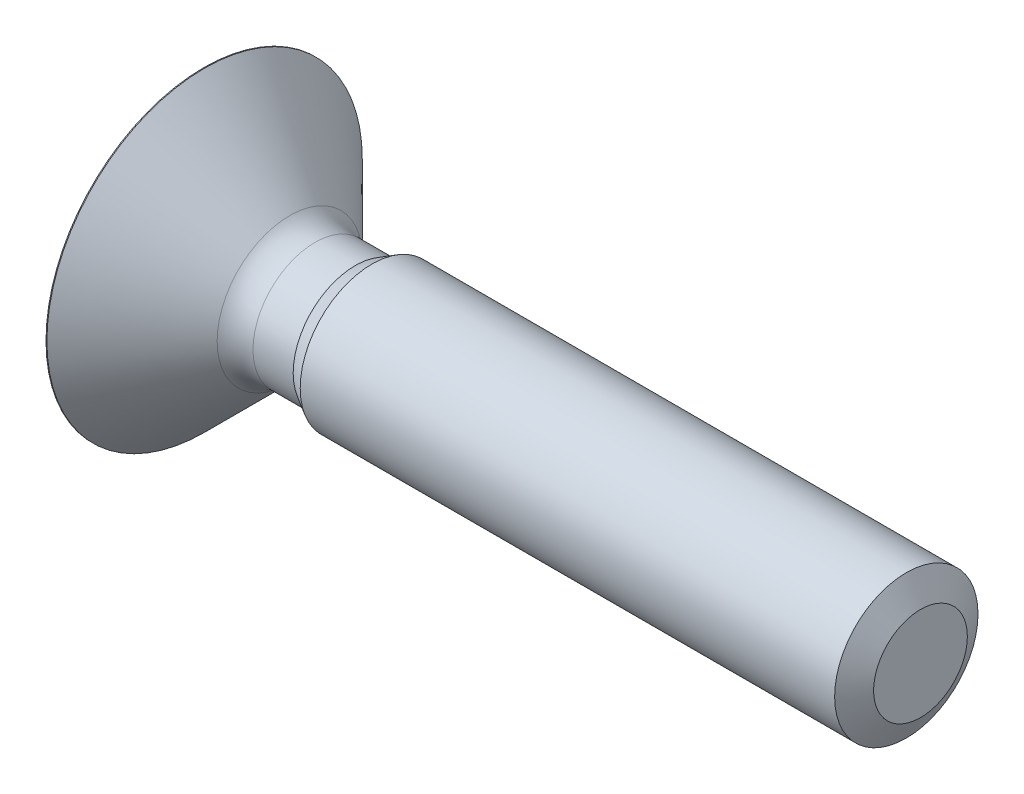
SolidWorks part; units mm, degrees
revolve "基体-旋转" add sketch "草图1" angle 360 about L0
sketch "草图1" plane through (0, 0, 0) normal (0, 0, 1) x (1, 0, 0)
  line L0 (0, 0) -> (4.4175, 0) construction
  line L1 (0, 0) -> (0, 2.2)
  line L2 (0, 2.2) -> (0.0124, 2.2)
  line L3 (0.0124, 2.2) -> (1.2, 1.0124)
  line L4 (1.5536, 0.866) -> (2.1144, 0.866)
  line L5 (2.1144, 0.866) -> (2.3464, 1)
  line L6 (2.3464, 1) -> (10, 1)
  line L7 (10, 1) -> (10, 0)
  line L8 (0, 0) -> (10, 0)
  arc A0 (1.5536, 0.866) -> (1.2, 1.0124) centre (1.5536, 1.366) cw
  point P12 (1.3464, 0.866)
  dimension "D2" = 0.5
  dimension "D1" = 1.732
  dimension "d" = 2
  dimension "dk" = 4.4
  dimension "D5" = 45
  dimension "a" = 1
  dimension "l" = 10
  dimension "D8" = 30
  dimension "k" = 1.2
ref_plane "前视" through (0, 0, 0) normal (0, 0, 1) x (1, 0, 0)
ref_plane "上视" through (0, 0, 0) normal (0, 1, 0) x (1, 0, 0)
ref_plane "右视" through (0, 0, 0) normal (1, 0, 0) x (0, 0, -1)
sketch "尺寸草图" plane through (0, 0, 0) normal (0, 0, 1) x (1, 0, 0)
  line L0 (0, 0) -> (10, 0)
  point P3 (1.2, 0)
  point P4 (1, 0)
  point P5 (2, 0)
  point P6 (4.4, 0)
  point P7 (8, 0)
  point P8 (3.5943, 0)
  point P9 (9.5, 0)
  point P10 (9.1, 0)
  point P11 (9.6, 0)
  dimension "d" = 2
  dimension "dk" = 4.4
  dimension "a" = 1
  dimension "l" = 10
  dimension "k" = 1.2
  dimension "r" = 0.5
  dimension "m" = 2
  dimension "h" = 0.9
  dimension "p" = 0.4
sketch "草图2" plane through (0, 0, 0) normal (0, 0, 1) x (1, 0, 0)
  line L0 (9.8022, 1) -> (10.2022, 1)
  line L1 (10.2022, 1) -> (10, 0.6536)
  line L2 (10, 0.6536) -> (9.8022, 1)
  line L3 (10, -1) -> (10, 1) construction
  line L6 (0, 0) -> (-0.4315, 0) construction
  dimension "D1" = 0.4
  dimension "D2" = 0.3464
  dimension "D3" = 1
  dimension "D4" = 60
revolve "切除-旋转1" cut sketch "草图2" angle 360 about L6
sketch "草图3" plane through (0, 0, 0) normal (-1, 0, 0) x (0, 0, 1)
  line L0 (0, 0) -> (1.6329, 0) construction
  line L1 (0, 0) -> (0, 0.8499) construction
  line L2 (-1.1, 0.2) -> (1.1, 0.2)
  line L3 (-1.1, 0.2) -> (-1.1, -0.2)
  line L4 (-1.1, -0.2) -> (1.1, -0.2)
  line L5 (1.1, 0.2) -> (1.1, -0.2)
  dimension "D1" = 0.4
  dimension "m" = 2.2
ref_plane "基准面1" through (1.2, 0, 0) normal (-1, 0, 0) x (0, 0, 1)
sketch "草图4" plane through (1.2, 0, 0) normal (-1, 0, 0) x (0, 0, 1)
  point P0 (0, 0)
loft "切除-放样1" cut profiles "草图3", "草图4"
pattern_circular "阵列(圆周)1" count 2 every 90 about axis through (0, 0, 0) along (1, 0, 0) of "切除-放样1"
equation "\"l@草图1\" = \"l@尺寸草图\""
equation "\"k@草图1\" = \"k@尺寸草图\""
equation "\"a@草图1\" = \"a@尺寸草图\""
equation "\"d@草图1\" = \"d@尺寸草图\""
equation "\"dk@草图1\" = \"dk@尺寸草图\""
equation "\"D2@草图1\" = \"r@尺寸草图\""
equation "\"m@草图3\" = \"dk@尺寸草图\"/2"
equation "\"D3@草图2\" = \"d@草图1\" / 2"
equation "\"D1@草图3\" = \"p@尺寸草图\""
equation "\"D1@草图1\" = \"d@尺寸草图\"*0.866"
equation "\"D2@草图2\" = \"p@尺寸草图\"*0.866"
equation "\"D1@草图2\" = \"p@尺寸草图\""
equation "\"a@尺寸草图\" = \"p@尺寸草图\"*2.5"
equation "\"m@尺寸草图\" = \"d@尺寸草图\""
